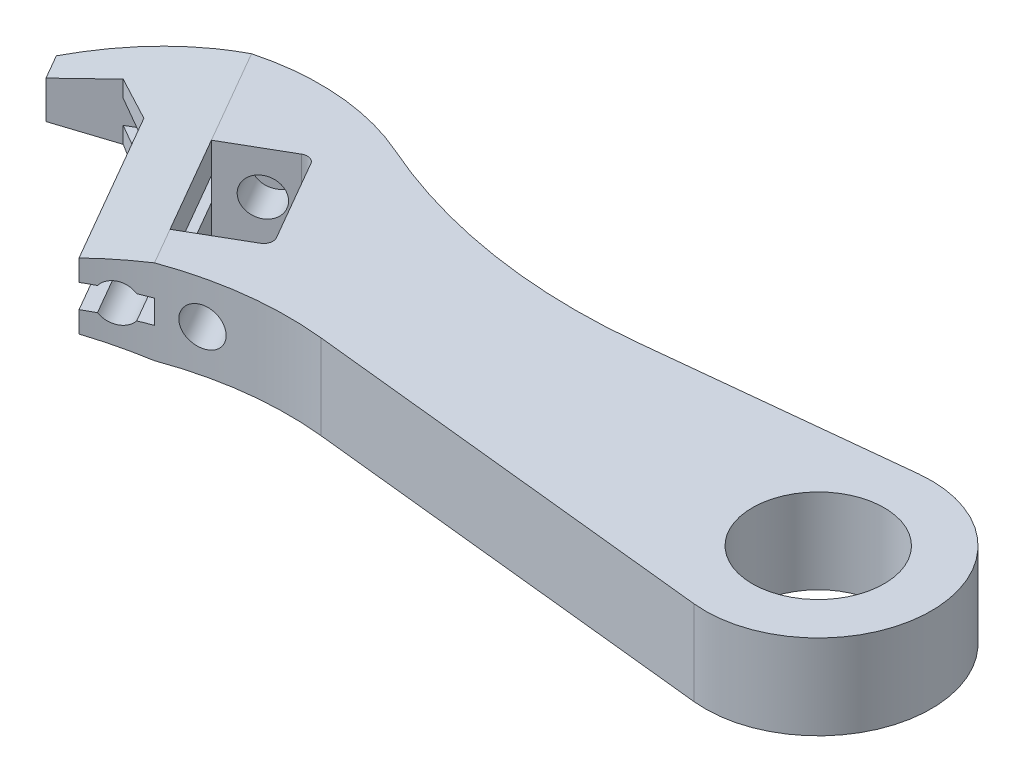
SolidWorks part; units mm, degrees
ref_plane "Front Plane" through (0, 0, 0) normal (0, 0, 1) x (1, 0, 0)
ref_plane "Top Plane" through (0, 0, 0) normal (0, 1, 0) x (1, 0, 0)
ref_plane "Right Plane" through (0, 0, 0) normal (1, 0, 0) x (0, 0, -1)
sketch "Sketch1" plane through (0, 0, 0) normal (0, 1, 0) x (1, 0, 0)
  line L0 (-28.2871, 9.093) -> (-1.2543, 11.9343)
  line L1 (-45.5418, -7.2795) -> (-1.2543, -11.9343)
  line L2 (25.0779, 0) -> (-99.2521, 0) construction
  line L3 (-62.5814, 9.0764) -> (-56.5814, -1.3159)
  line L4 (-56.5814, -1.3159) -> (-63.5096, -5.3159)
  line L5 (-63.5096, -5.3159) -> (-69.5096, 5.0764)
  line L6 (-69.5096, 5.0764) -> (-62.5814, 9.0764)
  line L7 (-75.3276, 15.1534) -> (-61.2511, -9.2278)
  line L8 (-66.7058, -11.78) -> (-76.1077, 4.5046)
  line L9 (-76.1077, 4.5046) -> (-81.3038, 7.5046)
  line L10 (-81.3038, 7.5046) -> (-86.5, 4.5046)
  line L11 (-86.5, 4.5046) -> (-88, 7.1027)
  line L12 (-81.3038, 7.5046) -> (-88.748, 20.3983) construction
  line L13 (-89.2059, 16) -> (-21.4804, 16) construction
  line L14 (-18.4207, -12) -> (11.6425, -12) construction
  line L15 (-78.2318, 14.1836) -> (-64.0436, -10.3911) construction
  line L16 (12, -12.8198) -> (12, 13.5746) construction
  line L17 (-88, 22.224) -> (-88, -5.3159) construction
  circle A0 centre (0, 0) radius 7
  arc A1 (-1.2543, -11.9343) -> (-1.2543, 11.9343) centre (0, 0) ccw
  arc A2 (-28.2871, 9.093) -> (-58.7831, 13.8719) centre (-34.5588, 68.7643) cw
  arc A3 (-45.5418, -7.2795) -> (-66.7058, -11.78) centre (-49.2003, -42.0877) ccw
  arc A4 (-88, 7.1027) -> (-58.7831, 13.8719) centre (-68.8766, -9) cw
  point P31 (-60.0455, -3.3159)
  point P32 (-66.0455, 7.0764)
  dimension "D1" = 14
  dimension "D2" = 5
  dimension "D5" = 60
  dimension "D6" = 35
  dimension "D13" = 25
  dimension "D3" = 12
  dimension "D4" = 6
  dimension "D7" = 8
  dimension "D8" = 6
  dimension "D9" = 3
  dimension "D10" = 30
  dimension "D11" = 15
  dimension "D12" = 6
  dimension "D14" = 16
  dimension "D15" = 8
  dimension "D16" = 4
  dimension "D17" = 12
  dimension "D18" = 0.49
  dimension "D19" = 28
  dimension "D20" = 60
  dimension "D21" = 19
  dimension "D22" = 6
  dimension "D23" = 3
  dimension "D24" = 12
  dimension "D25" = 100
extrude "Boss-Extrude1" add sketch "Sketch1" along normal mid plane 9 contours A4 L7 L6 L3 L4 A3 L1 A1 L0 A2 A0 | A4 L11 L10 L9 L8 A3 L7 L5
sketch "Sketch2" plane through (-19.5755, 0, -33.9058) normal (0.5, 0, 0.866) x (0.866, 0, -0.5)
  line L0 (0, 0) -> (-77.8625, 0) construction
  line L1 (-53.6589, 0) -> (-53.6589, 4.5) construction
  line L2 (-57.6589, 4.5) -> (-49.6589, 4.5) construction
  line L3 (-57.6589, 4.5) -> (-57.6589, -4.5) construction
  line L4 (-49.6589, 4.5) -> (-49.6589, -4.5) construction
  circle A0 centre (-53.6589, 0) radius 2
  point P5 (0, 0)
  dimension "D1" = 4
  dimension "D2" = 4
  dimension "D3" = 4
extrude "Cut-Extrude1" cut sketch "Sketch2" against normal blind 4 and the other way up to surface other way up to face at (-56.302, 0, 8.6915)
sketch "Sketch3" plane through (-23.5755, 0, -40.834) normal (0.5, 0, 0.866) x (0.866, 0, -0.5)
  line L0 (-72.6589, 0) -> (-56.4357, 0) construction
  line L1 (-72.6589, 4.5) -> (-72.6589, -4.5) construction
  line L2 (-66.6589, 1.25) -> (-62.2201, 1.25)
  line L4 (-66.6589, 4.5) -> (-66.6589, -4.5) construction
  line L5 (-66.6589, -1.25) -> (-62.2201, -1.25)
  line L6 (-59.0976, 1.25) -> (-57.6589, 1.25)
  line L7 (-57.6589, 1.25) -> (-57.6589, -1.25)
  line L8 (-59.0976, -1.25) -> (-57.6589, -1.25)
  circle A0 centre (-60.6589, 0) radius 2
  point P17 (-59.6695, -1.0863)
  line M10 (-66.6589, -4.5) -> (-66.6589, 4.5)
  dimension "D1" = 4
  dimension "D2" = 2.5
  dimension "D3" = 2.5
  dimension "D4" = 15
  dimension "D5" = 12
extrude "Cut-Extrude2" cut sketch "Sketch3" along normal up to next contours A0 L0 | L0 A0 | L0 A0 L2 M10 | L0 L5 A0 M10 | A0 L0 L7 L6 | L0 A0 L8 L7
sketch "Sketch4" plane through (-23.5755, 0, -40.834) normal (0.5, 0, 0.866) x (0.866, 0, -0.5)
  line L0 (-57.6589, 4.5) -> (-72.6589, 4.5)
  line L2 (-72.6589, 4.5) -> (-72.6589, -4.5) construction
  line L3 (-66.6589, 4.5) -> (-72.6589, 4.5) construction
  line L4 (-57.6589, 4.5) -> (-72.6589, 2)
  line L5 (-72.6589, 2) -> (-72.6589, 4.5)
  line L6 (0, 0) -> (-76.6034, 0) construction
  line L7 (-57.6589, -4.5) -> (-72.6589, -4.5)
  line L8 (-72.6589, -2) -> (-72.6589, -4.5)
  line L9 (-57.6589, -4.5) -> (-72.6589, -2)
  point P5 (0, 0)
  dimension "D1" = 15
  dimension "D2" = 2.5
extrude "Cut-Extrude3" cut sketch "Sketch4" against normal through all both and the other way through all
fillet "Fillet1" radius 1 2 edges at (-56.5814, 0, 1.3159) (-62.5814, 0, -9.0764)
